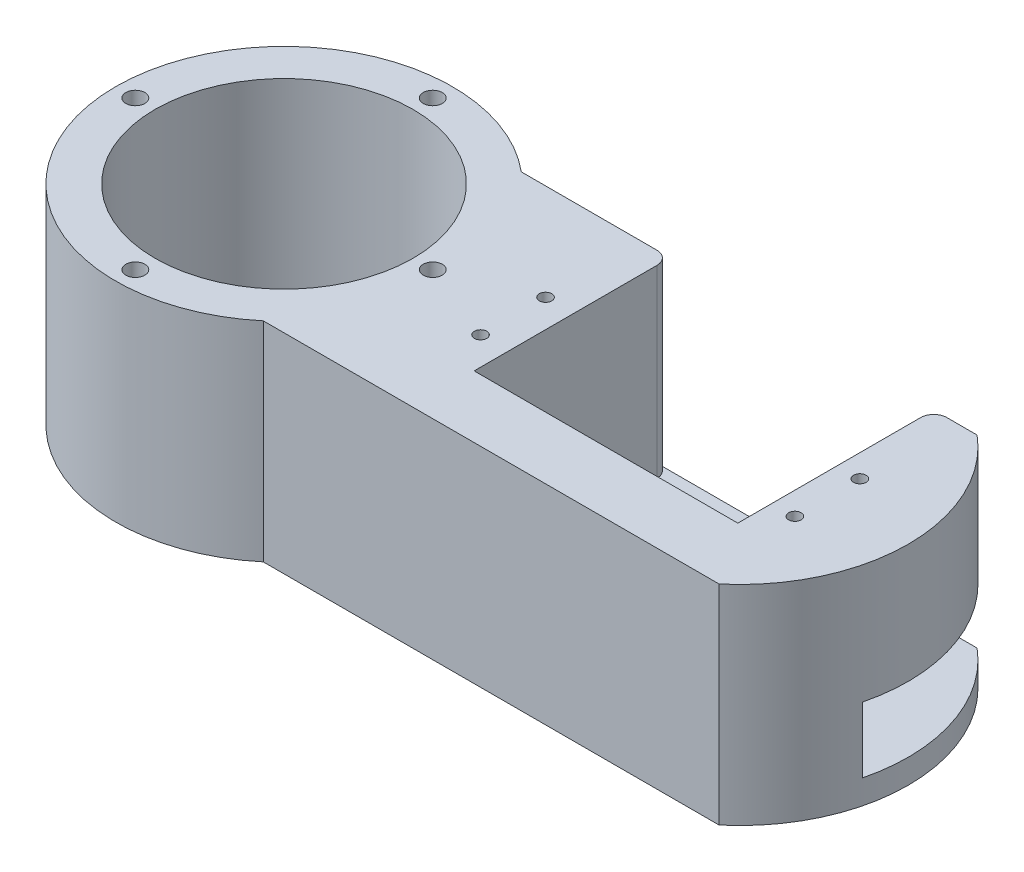
SolidWorks part; units mm, degrees
ref_plane "Front Plane" through (0, 0, 0) normal (0, 0, 1) x (1, 0, 0)
ref_plane "Top Plane" through (0, 0, 0) normal (0, 1, 0) x (1, 0, 0)
ref_plane "Right Plane" through (0, 0, 0) normal (1, 0, 0) x (0, 0, -1)
sketch "Sketch1" plane through (0, 0, 0) normal (0, 1, 0) x (1, 0, 0)
  line L0 (25.65, 0) -> (39.15, 0) construction
  line L1 (39.15, -10.195) -> (79.31, -10.195)
  line L2 (39.15, 10.195) -> (79.31, 10.195)
  line L3 (39.15, 10.195) -> (39.15, -10.195)
  line L4 (39.15, 0) -> (79.31, 0) construction
  line L5 (79.31, 10.195) -> (79.31, -10.195)
  line L6 (87.81, 17.8861) -> (87.81, -17.8861)
  line L7 (30.65, -18.695) -> (86.9869, -18.695)
  line L8 (30.65, 18.695) -> (30.65, -18.695)
  line L9 (30.65, 18.695) -> (86.9869, 18.695)
  line L10 (0, 25.65) -> (69.425, 25.65)
  line L11 (0, -25.65) -> (69.425, -25.65)
  line L12 (30.65, 18.695) -> (87.81, 18.695) construction
  line L13 (87.81, 18.695) -> (87.81, -18.695) construction
  line L14 (30.65, -18.695) -> (87.81, -18.695) construction
  circle A0 centre (0, 0) radius 15.65 construction
  circle A1 centre (16.6, 0) radius 0.95
  circle A2 centre (0, -16.6) radius 0.95
  circle A3 centre (-16.6, 0) radius 0.95
  circle A4 centre (0, 16.6) radius 0.95
  circle A5 centre (0, 0) radius 19.65
  circle A6 centre (0, 0) radius 4
  circle A7 centre (0, 0) radius 25.65
  circle A8 centre (69.425, 0) radius 25.65 construction
  arc A9 (69.425, 25.65) -> (69.425, -25.65) centre (69.425, 0) cw
  arc A10 (0, -25.65) -> (0, 25.65) centre (0, 0) cw
  point P14 (0, 0)
  point P28 (59.23, 0)
  point P29 (69.425, 0)
  dimension "D1" = 31.3
  dimension "D2" = 1.9
  dimension "D5" = 8
  dimension "D7" = 5
  dimension "D8" = 40.16
  dimension "D9" = 20.39
  dimension "D11" = 10.195
  dimension "D4" = 4
  dimension "D6" = 6
  dimension "D10" = 8.5
  dimension "D3" = 4
extrude "Boss-Extrude2" add sketch "Sketch1" along normal blind 3.7 contours A7 A5 | A5 A6 A1 A2 A3 A4 | A9 L10 A7 L11 L7 L8 L9 | A9 L9 L8 L7 L6 L2 L5 L1 L3 | L5 L2 L3 L1 | A9 L6
sketch "Sketch5" plane through (0, 3.7, 0) normal (0, 1, 0) x (1, 0, 0)
  line L0 (30.65, -18.695) -> (86.9869, -18.695) construction
  line L1 (30.65, 18.695) -> (30.65, -18.695) construction
  line L2 (69.425, 25.65) -> (0, 25.65)
  line L3 (0, -25.65) -> (69.425, -25.65)
  line L4 (39.15, -10.195) -> (79.31, -10.195)
  line L5 (79.31, -10.195) -> (79.31, 10.195)
  line L6 (79.31, 10.195) -> (39.15, 10.195)
  line L7 (39.15, 10.195) -> (39.15, -10.195)
  line L8 (39.15, -10.195) -> (79.31, -10.195)
  line L9 (79.31, -10.195) -> (79.31, 10.195)
  line L10 (79.31, 10.195) -> (39.15, 10.195)
  line L11 (39.15, 10.195) -> (39.15, -10.195)
  line L12 (69.425, 25.65) -> (0, 25.65)
  line L13 (0, -25.65) -> (69.425, -25.65)
  line L14 (30.65, 18.695) -> (86.9869, 18.695) construction
  line L15 (87.81, 17.8861) -> (87.81, -17.8861) construction
  line L16 (30.65, -18.695) -> (86.9869, -18.695)
  line L17 (30.65, 18.695) -> (30.65, -18.695)
  line L18 (30.65, 18.695) -> (86.9869, 18.695)
  line L19 (87.81, 17.8861) -> (87.81, -17.8861)
  circle A1 centre (0, 0) radius 4
  circle A2 centre (0, 0) radius 4
  circle A3 centre (0, 0) radius 19.65
  circle A4 centre (0, 0) radius 19.65
  circle A5 centre (0, 16.6) radius 0.95
  circle A6 centre (0, 16.6) radius 0.95
  circle A7 centre (-16.6, 0) radius 0.95
  circle A8 centre (-16.6, 0) radius 0.95
  circle A9 centre (0, -16.6) radius 0.95
  circle A10 centre (0, -16.6) radius 0.95
  circle A11 centre (16.6, 0) radius 0.95
  circle A12 centre (16.6, 0) radius 0.95
  circle A13 centre (0, 0) radius 25.65
  circle A14 centre (0, 0) radius 25.65
  arc A16 (69.425, -25.65) -> (69.425, 25.65) centre (69.425, 0) ccw
  arc A17 (0, 25.65) -> (0, -25.65) centre (0, 0) ccw
  arc A18 (69.425, -25.65) -> (69.425, 25.65) centre (69.425, 0) ccw
  arc A19 (0, 25.65) -> (0, -25.65) centre (0, 0) ccw
  arc M16 (69.425, -25.65) -> (69.425, 25.65) centre (69.425, 0) ccw
  line M17 (69.425, 25.65) -> (0, 25.65)
  arc M18 (0, 25.65) -> (0, -25.65) centre (0, 0) ccw
  line M19 (0, -25.65) -> (69.425, -25.65)
  dimension "D1" = 0
  dimension "D2" = 0
  dimension "D3" = 0
  dimension "D4" = 0
  dimension "D5" = 0
  dimension "D6" = 0
  dimension "D7" = 0
  dimension "D8" = 0
  dimension "D9" = 0
extrude "Boss-Extrude3" add sketch "Sketch5" along normal blind 28.1 contours A14 A4 M18 | L19 L18 L17 L16 L11 L10 L9 L8 M16 | A14 L16 L17 L18 M19 M16 M17 | L19 M16
sketch "Sketch6" plane through (0, 0, -10.195) normal (0, 0, 1) x (1, 0, 0)
  line L1 (39.15, 31.8) -> (79.31, 31.8)
  line L2 (39.15, 31.8) -> (39.15, 3.7)
  line L3 (39.15, 3.7) -> (79.31, 3.7)
  line L4 (79.31, 31.8) -> (79.31, 3.7)
extrude "Cut-Extrude1" cut sketch "Sketch6" against normal up to next
sketch "Sketch7" plane through (79.31, 0, 0) normal (-1, 0, 0) x (0, 0, 1)
  line L0 (10.195, 3.7) -> (-23.6687, 3.7) construction
  line L1 (-23.6687, 3.7) -> (-23.6687, 31.8) construction
  line L2 (6.195, 3.7) -> (-23.6687, 3.7)
  line L3 (6.195, 3.7) -> (6.195, 13.7)
  line L4 (6.195, 13.7) -> (-23.6687, 13.7)
  line L5 (-23.6687, 3.7) -> (-23.6687, 13.7)
  point P0 (6.195, 3.7)
  dimension "D1" = 4
  dimension "D2" = 10
extrude "Cut-Extrude2" cut sketch "Sketch7" against normal up to next
sketch "Sketch8" plane through (0, 31.8, 0) normal (0, 1, 0) x (1, 0, 0)
  line L0 (30.65, -18.695) -> (86.9869, -18.695) construction
  line L1 (30.65, 18.695) -> (30.65, -18.695) construction
  line L2 (69.425, 25.65) -> (0, 25.65)
  line L3 (0, -25.65) -> (69.425, -25.65)
  line L4 (39.15, -10.195) -> (79.31, -10.195)
  line L5 (79.31, -10.195) -> (79.31, 10.195)
  line L6 (79.31, 10.195) -> (39.15, 10.195)
  line L7 (39.15, 10.195) -> (39.15, -10.195)
  line L8 (39.15, -10.195) -> (79.31, -10.195)
  line L9 (79.31, -10.195) -> (79.31, 10.195)
  line L10 (79.31, 10.195) -> (39.15, 10.195)
  line L11 (39.15, 10.195) -> (39.15, -10.195)
  line L12 (69.425, 25.65) -> (0, 25.65)
  line L13 (0, -25.65) -> (69.425, -25.65)
  line L14 (30.65, 18.695) -> (86.9869, 18.695) construction
  line L15 (87.81, 17.8861) -> (87.81, -17.8861) construction
  line L16 (30.65, -18.695) -> (86.9869, -18.695)
  line L17 (30.65, 18.695) -> (30.65, -18.695)
  line L18 (30.65, 18.695) -> (86.9869, 18.695)
  line L19 (87.81, 17.8861) -> (87.81, -17.8861)
  line L20 (19.65, 0) -> (25.65, 0) construction
  circle A0 centre (22.65, 0) radius 1.45
  circle A1 centre (0, 0) radius 4
  circle A2 centre (0, 0) radius 4
  circle A3 centre (0, 0) radius 19.65
  circle A4 centre (0, 0) radius 19.65
  circle A5 centre (0, 16.6) radius 0.95
  circle A6 centre (0, 16.6) radius 0.95
  circle A7 centre (-16.6, 0) radius 0.95
  circle A8 centre (-16.6, 0) radius 0.95
  circle A9 centre (0, -16.6) radius 0.95
  circle A10 centre (0, -16.6) radius 0.95
  circle A11 centre (16.6, 0) radius 0.95
  circle A12 centre (16.6, 0) radius 0.95
  circle A13 centre (0, 0) radius 25.65
  circle A14 centre (0, 0) radius 25.65
  circle A15 centre (0, -22.65) radius 1.45
  arc A16 (69.425, -25.65) -> (69.425, 25.65) centre (69.425, 0) ccw
  arc A17 (0, 25.65) -> (0, -25.65) centre (0, 0) ccw
  arc A18 (69.425, -25.65) -> (69.425, 25.65) centre (69.425, 0) ccw
  arc A19 (0, 25.65) -> (0, -25.65) centre (0, 0) ccw
  circle A20 centre (-22.65, 0) radius 1.45
  circle A21 centre (0, 22.65) radius 1.45
  point P50 (0, 0)
  dimension "D10" = 2.9
  dimension "D1" = 0
  dimension "D2" = 0
  dimension "D3" = 0
  dimension "D4" = 0
  dimension "D5" = 0
  dimension "D6" = 0
  dimension "D7" = 0
  dimension "D8" = 0
  dimension "D9" = 0
  dimension "D11" = 4
extrude "Cut-Extrude3" cut sketch "Sketch8" against normal blind 15 contours A20 | A21 | A0 | A15
sketch "Sketch9" plane through (0, 31.8, 0) normal (0, 1, 0) x (1, 0, 0)
  line L0 (30.65, -18.695) -> (86.9869, -18.695) construction
  line L1 (30.65, 18.695) -> (30.65, -18.695) construction
  line L2 (69.425, 25.65) -> (0, 25.65)
  line L3 (0, -25.65) -> (69.425, -25.65)
  line L4 (39.15, -10.195) -> (79.31, -10.195)
  line L5 (79.31, -10.195) -> (79.31, 10.195)
  line L6 (79.31, 10.195) -> (39.15, 10.195)
  line L7 (39.15, 10.195) -> (39.15, -10.195)
  line L8 (39.15, -10.195) -> (79.31, -10.195)
  line L9 (79.31, -10.195) -> (79.31, 10.195)
  line L10 (79.31, 10.195) -> (39.15, 10.195)
  line L11 (39.15, 10.195) -> (39.15, -10.195)
  line L12 (69.425, 25.65) -> (0, 25.65)
  line L13 (0, -25.65) -> (69.425, -25.65)
  line L14 (30.65, 18.695) -> (86.9869, 18.695) construction
  line L15 (87.81, 17.8861) -> (87.81, -17.8861) construction
  line L16 (30.65, -18.695) -> (86.9869, -18.695)
  line L17 (30.65, 18.695) -> (30.65, -18.695)
  line L18 (30.65, 18.695) -> (86.9869, 18.695)
  line L19 (87.81, 17.8861) -> (87.81, -17.8861)
  line L20 (30.65, 0) -> (87.81, 0) construction
  line L21 (58.8184, 18.695) -> (58.8184, -18.695) construction
  circle A0 centre (34.88, -4.95) radius 0.95
  circle A1 centre (0, 0) radius 4
  circle A2 centre (0, 0) radius 4
  circle A3 centre (0, 0) radius 19.65
  circle A4 centre (0, 0) radius 19.65
  circle A5 centre (0, 16.6) radius 0.95
  circle A6 centre (0, 16.6) radius 0.95
  circle A7 centre (-16.6, 0) radius 0.95
  circle A8 centre (-16.6, 0) radius 0.95
  circle A9 centre (0, -16.6) radius 0.95
  circle A10 centre (0, -16.6) radius 0.95
  circle A11 centre (16.6, 0) radius 0.95
  circle A12 centre (16.6, 0) radius 0.95
  circle A13 centre (0, 0) radius 25.65
  circle A14 centre (0, 0) radius 25.65
  circle A15 centre (34.88, 4.95) radius 0.95
  arc A16 (69.425, -25.65) -> (69.425, 25.65) centre (69.425, 0) ccw
  arc A17 (0, 25.65) -> (0, -25.65) centre (0, 0) ccw
  arc A18 (69.425, -25.65) -> (69.425, 25.65) centre (69.425, 0) ccw
  arc A19 (0, 25.65) -> (0, -25.65) centre (0, 0) ccw
  circle A20 centre (82.7569, -4.95) radius 0.95
  circle A21 centre (82.7569, 4.95) radius 0.95
  dimension "D10" = 1.9
  dimension "D11" = 4.27
  dimension "D12" = 4.95
  dimension "D1" = 0
  dimension "D2" = 0
  dimension "D3" = 0
  dimension "D4" = 0
  dimension "D5" = 0
  dimension "D6" = 0
  dimension "D7" = 0
  dimension "D8" = 0
  dimension "D9" = 0
extrude "Cut-Extrude4" cut sketch "Sketch9" against normal blind 12 contours A0 | A15 | A21 | A20
sketch "Sketch12" plane through (0, 31.8, 0) normal (0, 1, 0) x (1, 0, 0)
  line L0 (0, 25.65) -> (69.425, 25.65)
  line L1 (39.15, 25.65) -> (69.425, 25.65) construction
  line L2 (39.15, 19.65) -> (14.5613, 19.65) construction
  line L3 (85.9114, 19.65) -> (16.4864, 19.65)
  line L4 (-17.49, 0) -> (17.49, 0) construction
  line L5 (0, -25.65) -> (69.425, -25.65)
  line L6 (85.9114, -19.65) -> (16.4864, -19.65)
  circle A0 centre (0, 0) radius 19.65 construction
  arc A1 (0, 25.65) -> (16.4864, 19.65) centre (0, 0) cw
  arc A2 (94.3157, -6.195) -> (69.425, 25.65) centre (69.425, 0) ccw construction
  arc A3 (69.425, 25.65) -> (85.9114, 19.65) centre (69.425, 0) cw
  arc A4 (69.425, -25.65) -> (85.9114, -19.65) centre (69.425, 0) ccw
  arc A5 (0, -25.65) -> (16.4864, -19.65) centre (0, 0) ccw
extrude "Cut-Extrude5" cut sketch "Sketch12" against normal through all
fillet "Fillet1" radius 2 2 edges at (79.31, 22.75, -19.65) (39.15, 17.75, -19.65)
